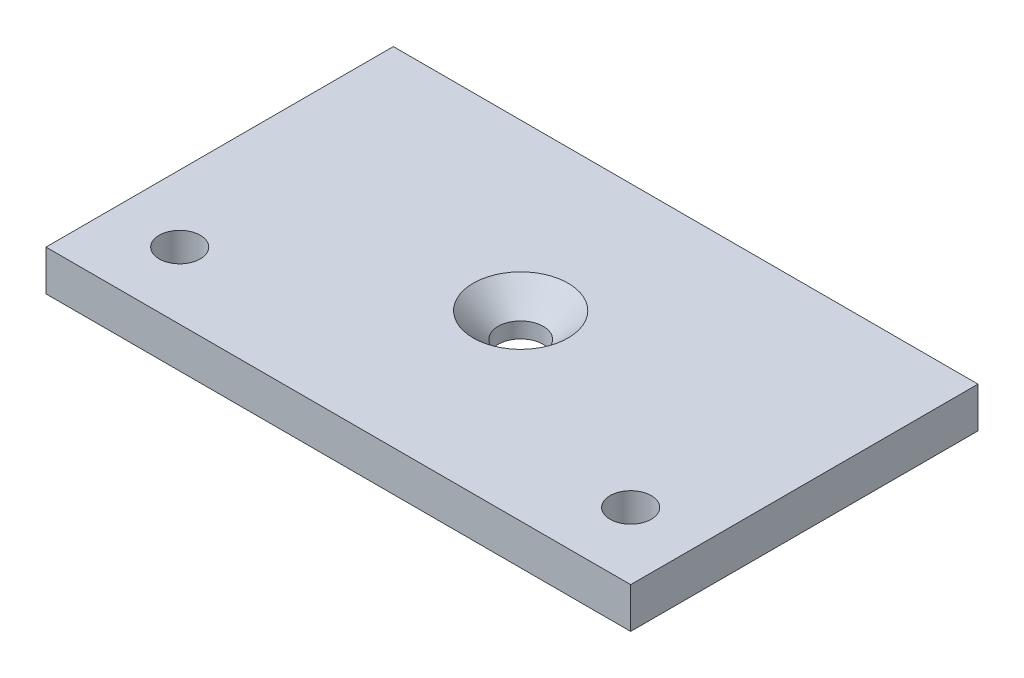
SolidWorks part; units mm, degrees
ref_plane "Front Plane" through (0, 0, 0) normal (0, 0, 1) x (1, 0, 0)
ref_plane "Top Plane" through (0, 0, 0) normal (0, 1, 0) x (1, 0, 0)
ref_plane "Right Plane" through (0, 0, 0) normal (1, 0, 0) x (0, 0, -1)
sketch "Sketch1" plane through (0, 0, 0) normal (0, 1, 0) x (1, 0, 0)
  line L1 (-19.475, -19.975) -> (19.475, -19.975)
  line L2 (-19.475, -19.975) -> (-19.475, 19.975)
  line L3 (-19.475, 19.975) -> (19.475, 19.975)
  line L4 (19.475, -19.975) -> (19.475, 19.975)
  line L5 (-19.475, -19.975) -> (19.475, 19.975) construction
  line L6 (-19.475, 19.975) -> (19.475, -19.975) construction
  line L7 (-25.25, -25.75) -> (25.25, -25.75)
  line L8 (-25.25, -25.75) -> (-25.25, 25.75)
  line L9 (-25.25, 25.75) -> (25.25, 25.75)
  line L10 (25.25, -25.75) -> (25.25, 25.75)
  line L11 (-25.25, -25.75) -> (25.25, 25.75) construction
  line L12 (-25.25, 25.75) -> (25.25, -25.75) construction
  circle A0 centre (-19.475, 19.975) radius 1.775
  circle A1 centre (19.475, 19.975) radius 1.775
  circle A2 centre (19.475, -19.975) radius 1.775
  circle A3 centre (-19.475, -19.975) radius 1.775
  point P0 (0, 0)
  point P10 (0, 0)
  dimension "D1" = 3.55
  dimension "D2" = 43.5
  dimension "D3" = 42.5
  dimension "D4" = 35.4
  dimension "D5" = 36.4
  dimension "D6" = 4
  dimension "D7" = 4
extrude "Boss-Extrude1" add sketch "Sketch1" along normal blind 3.5 contours L7 L10 L9 L8 A3 L2 A0 L3 A1 L4 A2 L1 | A3 L1 A2 L4 A1 L3 A0 L2
sketch "Sketch2" plane through (0, 3.5, 0) normal (0, 1, 0) x (1, 0, 0)
  line L0 (0, 10) -> (0, -10)
  circle A0 centre (0, 10) radius 3
  circle A1 centre (0, -10) radius 3
  point P4 (0, 0)
  dimension "D1" = 6
  dimension "D2" = 6
hole_wizard "CSK for M3.5 Flat Head Machine Screw1" positions "Sketch3" profile "Sketch4" countersink size "M3.5" standard "ANSI Metric" end condition through all
sketch "Sketch3" plane through (0, 3.5, 0) normal (0, 1, 0) x (1, 0, 0)
  point P0 (0, 10)
  point P3 (0, -10)
sketch "Sketch4" plane through (0, 3.5, -10) normal (1, 0, 0) x (0, 0, 1)
  line L0 (0, 0) -> (0, 3.5)
  line L1 (0, 3.5) -> (1.95, 3.5)
  line L2 (1.95, 3.5) -> (1.95, 2.15)
  line L3 (1.95, 2.15) -> (4.1, 0)
  line L5 (4.1, 0) -> (0, 0)
  line L6 (-1.95, 2.15) -> (-4.1, 0) construction
  line L11 (0, -6.35) -> (0, 107.95) construction
  dimension "Thru Hole Dia." = 3.9
  dimension "Thru Hole Depth" = 3.5
  dimension "Near C'Sink Dia." = 8.2
  dimension "Near C'Sink Angle" = 90
ref_plane "Plane1" through (0, 0, -4.25) normal (0, 0, 1) x (1, 0, 0)
split "Split1" trim tools "Plane1" bodies to split 102 resulting bodies 105
